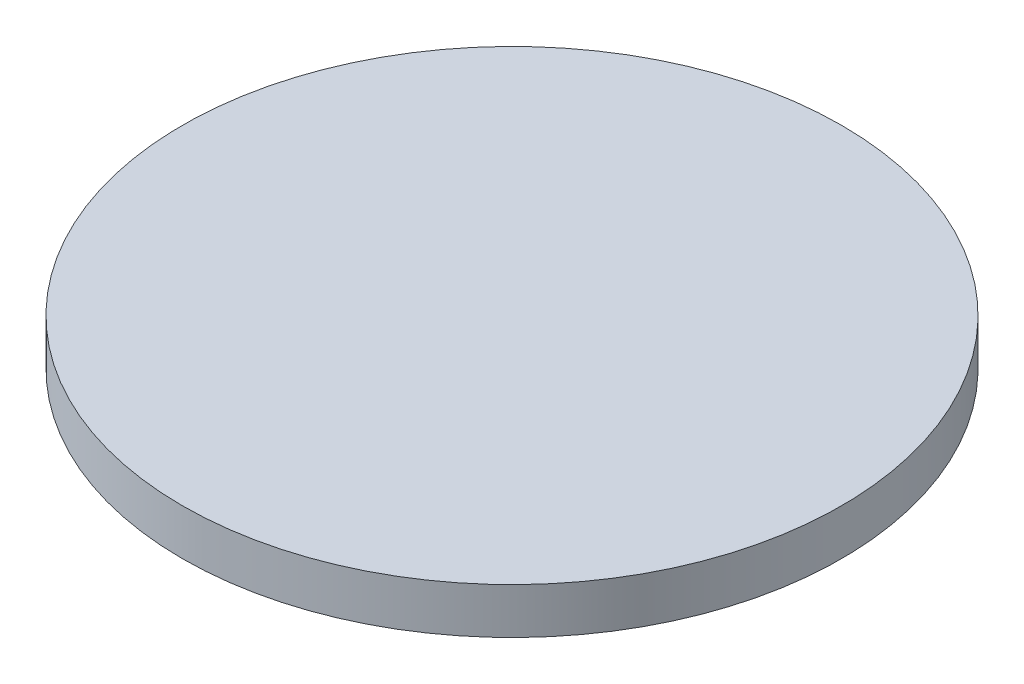
SolidWorks part; units mm, degrees
ref_plane "Front Plane" through (0, 0, 0) normal (0, 0, 1) x (1, 0, 0)
ref_plane "Top Plane" through (0, 0, 0) normal (0, 1, 0) x (1, 0, 0)
ref_plane "Right Plane" through (0, 0, 0) normal (1, 0, 0) x (0, 0, -1)
sketch "Sketch1" plane through (0, 0, 0) normal (0, 1, 0) x (1, 0, 0)
  circle A0 centre (0, 0) radius 11.5
  dimension "D1" = 23
extrude "Boss-Extrude1" add sketch "Sketch1" along normal blind 1.6
